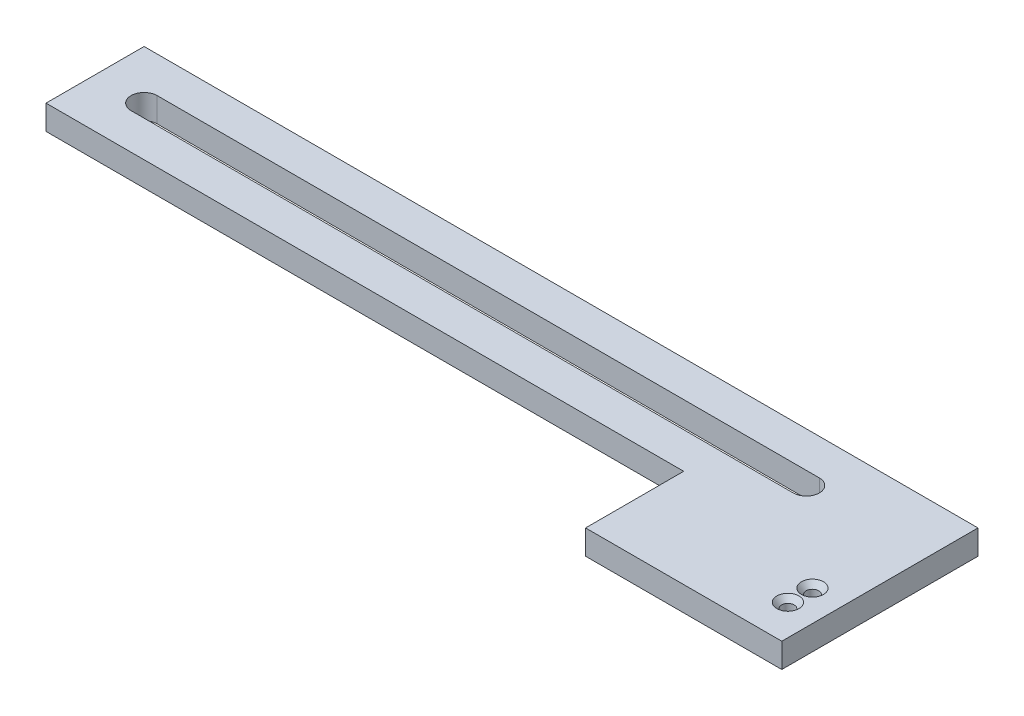
SolidWorks part; units mm, degrees
ref_plane "Front Plane" through (0, 0, 0) normal (0, 0, 1) x (1, 0, 0)
ref_plane "Top Plane" through (0, 0, 0) normal (0, 1, 0) x (1, 0, 0)
ref_plane "Right Plane" through (0, 0, 0) normal (1, 0, 0) x (0, 0, -1)
sketch "Sketch1" plane through (0, 0, 0) normal (0, 1, 0) x (1, 0, 0)
  line L0 (0, 0) -> (215.9, 0)
  line L1 (215.9, 0) -> (215.9, -50.8)
  line L2 (215.9, -50.8) -> (165.1, -50.8)
  line L3 (165.1, -50.8) -> (165.1, -25.4)
  line L4 (165.1, -25.4) -> (0, -25.4)
  line L5 (0, -25.4) -> (0, 0)
  dimension "D1" = 215.9
  dimension "D2" = 25.4
  dimension "D3" = 50.8
  dimension "D4" = 50.8
extrude "Boss-Extrude1" add sketch "Sketch1" along normal blind 6.35
sketch "Sketch2" plane through (0, 6.35, 0) normal (0, 1, 0) x (1, 0, 0)
  line L0 (184.15, -12.7) -> (12.7, -12.7) construction
  line L1 (184.15, -16.0782) -> (12.7, -16.0782)
  line L2 (184.15, -9.3218) -> (12.7, -9.3218)
  line L3 (215.9, -50.8) -> (215.9, 0) construction
  line L4 (215.9, 0) -> (0, 0) construction
  arc A0 (184.15, -16.0782) -> (184.15, -9.3218) centre (184.15, -12.7) ccw
  arc A1 (12.7, -9.3218) -> (12.7, -16.0782) centre (12.7, -12.7) ccw
  point P2 (98.425, -12.7)
  dimension "D1" = 31.75
  dimension "D2" = 12.7
extrude "Cut-Extrude1" cut sketch "Sketch2" against normal through all
hole_wizard "CSK for #4 Flat Head Machine Screw1" positions "Sketch4" profile "Sketch3" countersink size "#4" standard "ANSI Inch" end condition through all
sketch "Sketch4" plane through (0, 6.35, 0) normal (0, 1, 0) x (1, 0, 0)
  point P0 (207.9625, -34.925)
  point P3 (207.9625, -41.275)
sketch "Sketch3" plane through (207.9625, 6.35, 34.925) normal (1, 0, 0) x (0, 0, 1)
  line L0 (0, 0) -> (0, 6.35)
  line L1 (0, 6.35) -> (1.6319, 6.35)
  line L2 (1.6319, 6.35) -> (1.6319, 1.4098)
  line L3 (1.6319, 1.4098) -> (2.8575, 0)
  line L5 (2.8575, 0) -> (0, 0)
  line L6 (-1.6319, 1.4098) -> (-2.8575, 0) construction
  line L11 (0, -6.35) -> (0, 107.95) construction
  dimension "Thru Hole Dia." = 3.2639
  dimension "Thru Hole Depth" = 6.35
  dimension "Near C'Sink Dia." = 5.715
  dimension "Near C'Sink Angle" = 82
